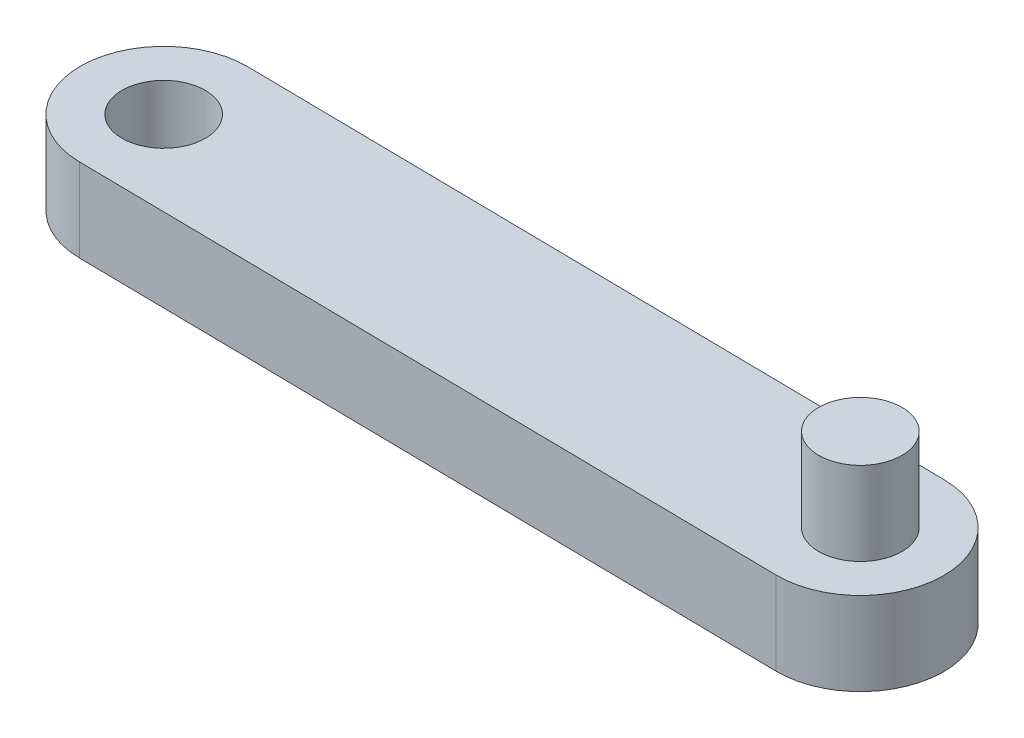
SolidWorks part; units mm, degrees
ref_plane "Front Plane" through (0, 0, 0) normal (0, 0, 1) x (1, 0, 0)
ref_plane "Top Plane" through (0, 0, 0) normal (0, 1, 0) x (1, 0, 0)
ref_plane "Right Plane" through (0, 0, 0) normal (1, 0, 0) x (0, 0, -1)
sketch "Sketch1" plane through (0, 0, 0) normal (0, 1, 0) x (1, 0, 0)
  line L0 (-14.5716, 1.7071) -> (27.8284, 1.1375) construction
  line L1 (-14.5044, 6.7067) -> (27.8956, 6.137)
  line L2 (-14.6388, -3.2924) -> (27.7612, -3.8621)
  arc A0 (-14.5044, 6.7067) -> (-14.6388, -3.2924) centre (-14.5716, 1.7071) ccw
  arc A1 (27.7612, -3.8621) -> (27.8956, 6.137) centre (27.8284, 1.1375) ccw
  circle A2 centre (-14.5716, 1.7071) radius 2.5
  point P2 (6.6284, 1.4223)
  dimension "D2" = 5
  dimension "D1" = 42.4
  dimension "D3" = 10
  dimension "D4" = 0
extrude "Boss-Extrude1" add sketch "Sketch1" along normal blind 5
sketch "Sketch2" plane through (0, 5, 0) normal (0, 1, 0) x (1, 0, 0)
  line L0 (-14.6388, -3.2924) -> (27.7612, -3.8621) construction
  circle A0 centre (27.8284, 1.1375) radius 2.5
  circle A1 centre (-14.5716, 1.7071) radius 2.5 construction
  dimension "D2" = 5
  dimension "D1" = 42.4
  dimension "D3" = 5
extrude "Boss-Extrude2" add sketch "Sketch2" along normal blind 5
